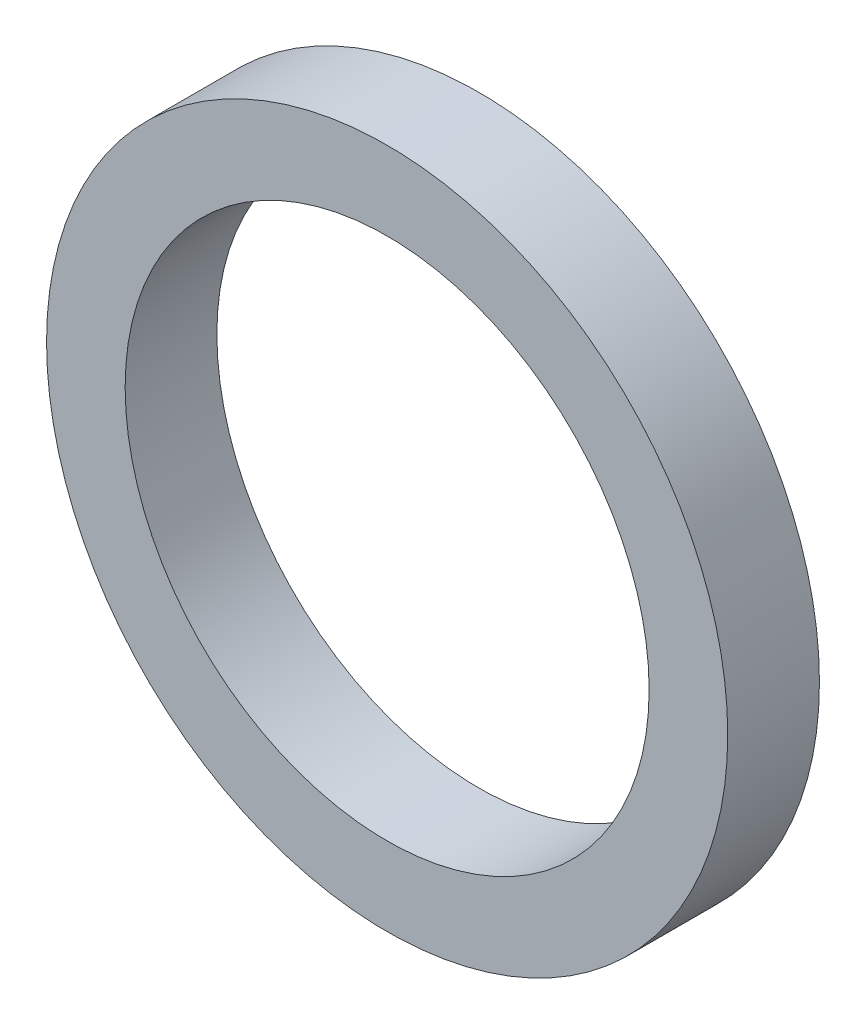
SolidWorks part; units mm, degrees
ref_plane "Front Plane" through (0, 0, 0) normal (0, 0, 1) x (1, 0, 0)
ref_plane "Top Plane" through (0, 0, 0) normal (0, 1, 0) x (1, 0, 0)
ref_plane "Right Plane" through (0, 0, 0) normal (1, 0, 0) x (0, 0, -1)
sketch "Sketch1" plane through (0, 0, 0) normal (0, 0, 1) x (1, 0, 0)
  circle A0 centre (0, 0) radius 26
  circle A1 centre (0, 0) radius 20
  dimension "D1" = 40
  dimension "D2" = 52
extrude "Boss-Extrude1" add sketch "Sketch1" along normal blind 7
